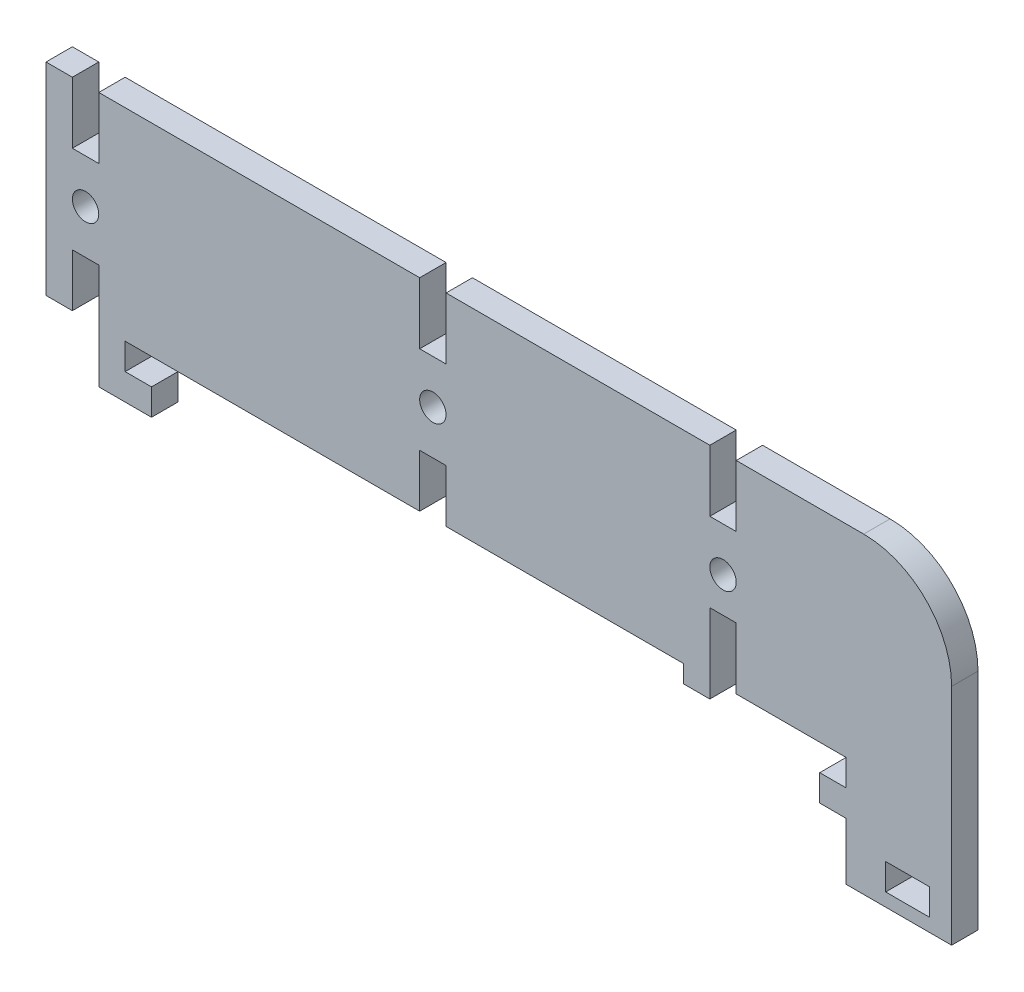
SolidWorks part; units mm, degrees
ref_plane "前视基准面" through (0, 0, 0) normal (0, 0, 1) x (1, 0, 0)
ref_plane "上视基准面" through (0, 0, 0) normal (0, 1, 0) x (1, 0, 0)
ref_plane "右视基准面" through (0, 0, 0) normal (1, 0, 0) x (0, 0, -1)
other "Configuration Table"
sketch "草图1" plane through (0, 0, 0) normal (0, 0, 1) x (1, 0, 0)
  line L0 (0, 63.17) -> (0, 40.17)
  line L1 (0, 40.17) -> (3, 40.17)
  line L2 (3, 40.17) -> (3, 46.17)
  line L3 (3, 46.17) -> (6, 46.17)
  line L4 (6, 46.17) -> (6, 34.17)
  line L5 (6, 34.17) -> (12, 34.17)
  line L6 (12, 34.17) -> (12, 37.17)
  line L7 (12, 37.17) -> (9, 37.17)
  line L8 (9, 37.17) -> (9, 40.17)
  line L9 (0, 63.17) -> (3, 63.17)
  line L10 (3, 63.17) -> (3, 56.17)
  line L11 (3, 56.17) -> (6, 56.17)
  line L12 (6, 56.17) -> (6, 63.17)
  line L13 (6, 63.17) -> (42.5, 63.17)
  line L14 (42.5, 63.17) -> (42.5, 56.17)
  line L15 (42.5, 56.17) -> (45.5, 56.17)
  line L16 (45.5, 56.17) -> (45.5, 63.17)
  line L17 (45.5, 63.17) -> (75.5, 63.17)
  line L18 (75.5, 63.17) -> (75.5, 56.17)
  line L19 (75.5, 56.17) -> (78.5, 56.17)
  line L20 (78.5, 56.17) -> (78.5, 63.17)
  line L21 (78.5, 63.17) -> (93, 63.17)
  line L22 (93, 63.17) -> (93, 53.17) construction
  line L23 (93, 53.17) -> (103, 53.17) construction
  line L24 (103, 53.17) -> (103, 27.67)
  line L25 (42.5, 56.17) -> (42.5, 17.8283) construction
  line L26 (45.5, 56.17) -> (45.5, 6.1879) construction
  line L27 (75.5, 56.17) -> (75.5, -19.9566) construction
  line L28 (78.5, 56.17) -> (78.5, -30.2144) construction
  line L29 (9, 40.17) -> (42.5, 40.17)
  line L30 (42.5, 40.17) -> (42.5, 46.17)
  line L31 (42.5, 46.17) -> (45.5, 46.17)
  line L32 (45.5, 46.17) -> (45.5, 40.17)
  line L33 (45.5, 40.17) -> (72.5, 40.17)
  line L34 (72.5, 40.17) -> (72.5, 38.17)
  line L35 (72.5, 38.17) -> (75.5, 38.17)
  line L36 (75.5, 38.17) -> (75.5, 47.17)
  line L37 (75.5, 47.17) -> (78.5, 47.17)
  line L38 (78.5, 47.17) -> (78.5, 40.17)
  line L39 (103, 27.67) -> (91, 27.67)
  line L40 (91, 27.67) -> (91, 34.17)
  line L41 (91, 34.17) -> (88, 34.17)
  line L42 (88, 34.17) -> (88, 37.17)
  line L43 (88, 37.17) -> (91, 37.17)
  line L44 (91, 37.17) -> (91, 40.17)
  line L45 (91, 40.17) -> (78.5, 40.17)
  line L46 (103, 27.67) -> (103, 29.17) construction
  line L47 (103, 29.17) -> (100.5, 29.17) construction
  line L48 (100.5, 29.17) -> (100.5, 32.17)
  line L49 (100.5, 32.17) -> (95.5, 32.17)
  line L50 (95.5, 32.17) -> (95.5, 29.17)
  line L51 (95.5, 29.17) -> (100.5, 29.17)
  line L52 (4.5, 56.17) -> (4.5, 51.17) construction
  line L53 (44, 56.17) -> (44, 51.17) construction
  line L54 (77, 56.17) -> (77, 51.17) construction
  arc A0 (93, 63.17) -> (103, 53.17) centre (93, 53.17) cw
  circle A1 centre (4.5, 51.17) radius 1.5
  circle A2 centre (44, 51.17) radius 1.5
  circle A3 centre (77, 51.17) radius 1.5
  point P61 (1.5, 40.17)
  point P62 (100.0711, 60.241)
  dimension "D1" = 7
  dimension "D2" = 23
  dimension "D3" = 6
  dimension "D4" = 3
  dimension "D5" = 3
  dimension "D6" = 3
  dimension "D7" = 6
  dimension "D8" = 12
  dimension "D9" = 36.5
  dimension "D10" = 3
  dimension "D11" = 30
  dimension "D12" = 3
  dimension "D13" = 14.5
  dimension "D14" = 10
  dimension "D15" = 103
  dimension "D16" = 2.5
  dimension "D17" = 1.5
  dimension "D18" = 3
  dimension "D19" = 6.5
  dimension "D20" = 3
  dimension "D21" = 3
extrude "凸台-拉伸1" add sketch "草图1" along normal blind 3
